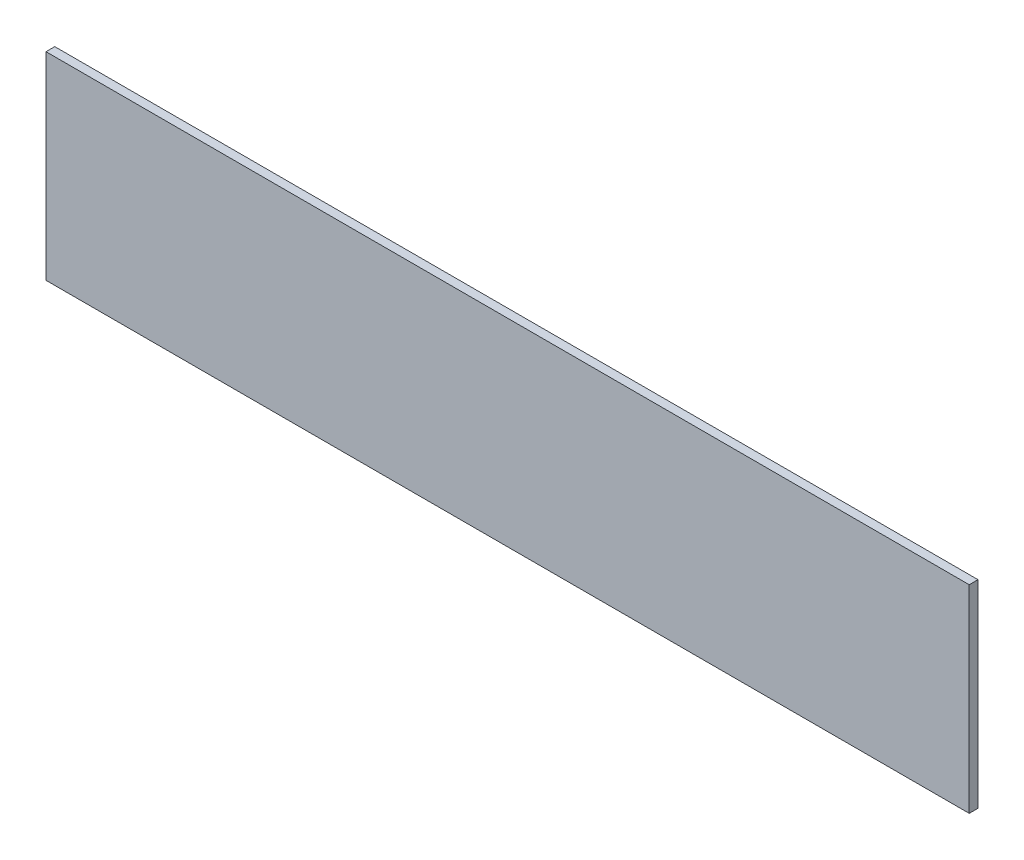
SolidWorks part; units mm, degrees
ref_plane "Front Plane" through (0, 0, 0) normal (0, 0, 1) x (1, 0, 0)
ref_plane "Top Plane" through (0, 0, 0) normal (0, 1, 0) x (1, 0, 0)
ref_plane "Right Plane" through (0, 0, 0) normal (1, 0, 0) x (0, 0, -1)
sketch "Sketch1" plane through (0, 0, 0) normal (0, 0, 1) x (1, 0, 0)
  line L1 (0, 0) -> (200, 0)
  line L2 (0, 0) -> (0, 42.9)
  line L3 (0, 42.9) -> (200, 42.9)
  line L4 (200, 0) -> (200, 42.9)
  dimension "D1" = 200
  dimension "D2" = 42.9
extrude "Boss-Extrude1" add sketch "Sketch1" along normal blind 1.9
